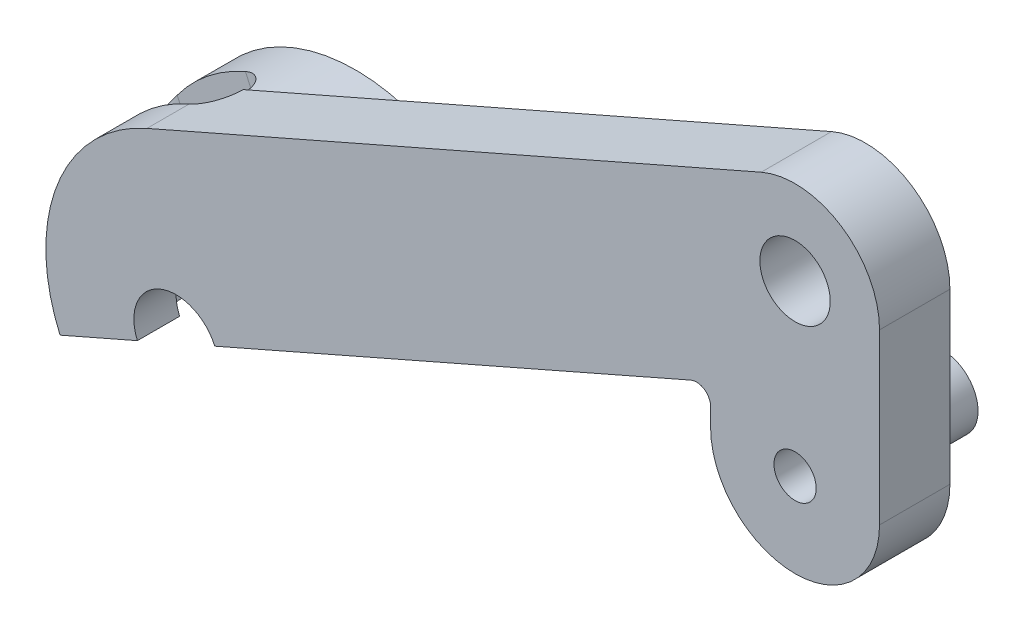
SolidWorks part; units mm, degrees
ref_plane "Plano frontal" through (0, 0, 0) normal (0, 0, 1) x (1, 0, 0)
ref_plane "Plano superior" through (0, 0, 0) normal (0, 1, 0) x (1, 0, 0)
ref_plane "Plano direito" through (0, 0, 0) normal (1, 0, 0) x (0, 0, -1)
sketch "Esboço7" plane through (0, 0, 0) normal (0, 0, 1) x (1, 0, 0)
  line L0 (0, 0) -> (0, -12) construction
  line L1 (6, 0) -> (6, -12)
  line L2 (-7.4014, -9.7942) -> (-41.2219, -24.6148)
  line L3 (0, 0) -> (-50.3755, -22.0751) construction
  line L4 (-46.1864, -20.7604) -> (-43.9697, -25.8189) construction
  line L5 (-2.4082, 5.4955) -> (-46.0383, -13.6238)
  line L6 (-6, -10.7101) -> (-6, -12)
  line L7 (-42.0163, -22.7728) -> (-47.4902, -25.2194) construction
  line L8 (-46.7174, -27.023) -> (-52.213, -29.4312)
  circle A0 centre (0, 0) radius 2.5
  arc A1 (-6, -12) -> (6, -12) centre (0, -12) ccw
  arc A2 (6, 0) -> (-2.4082, 5.4955) centre (0, 0) ccw
  arc A3 (-46.0383, -13.6238) -> (-52.213, -29.4312) centre (-41.2219, -24.6148) ccw
  arc A5 (-41.2219, -24.6148) -> (-46.7174, -27.023) centre (-43.9697, -25.8189) ccw
  arc A6 (-6, -10.7101) -> (-7.4014, -9.7942) centre (-7, -10.7101) ccw
  point P4 (0, -6)
  point P11 (-25.1877, -11.0376)
  dimension "D1" = 1
extrude "Ressalto-extrusão1" add sketch "Esboço7" along normal blind 5
sketch "Esboço8" plane through (0, 0, 0) normal (0, 0, -1) x (-1, 0, 0)
  circle A0 centre (0, -12) radius 2.5
extrude "Ressalto-extrusão2" add sketch "Esboço8" along normal blind 5.5
sketch "Esboço9" plane through (0, 0, -5.5) normal (0, 0, -1) x (-1, 0, 0)
  circle A0 centre (0, -12) radius 1.5
extrude "Corte-extrusão4" cut sketch "Esboço9" against normal blind 25
sketch "Esboço10" plane through (0, 0, 0) normal (0, 0, -1) x (-1, 0, 0)
  line L0 (46.7174, -27.023) -> (52.213, -29.4312)
  line L1 (41.2219, -24.6148) -> (30.2309, -19.7984)
  line L2 (41.2219, -24.6148) -> (7.4014, -9.7942) construction
  arc A0 (52.213, -29.4312) -> (30.2309, -19.7984) centre (41.2219, -24.6148) ccw
  arc A1 (46.7174, -27.023) -> (41.2219, -24.6148) centre (43.9697, -25.8189) ccw
extrude "Ressalto-extrusão3" add sketch "Esboço10" along normal blind 5
sketch "Esboço11" plane through (-2.4082, 5.4955, 0) normal (-0.4014, 0.9159, 0) x (-0.9159, -0.4014, 0)
  line L0 (47.6354, 0) -> (53.6354, 0) construction
  line L1 (47.6354, 5) -> (47.6354, -5) construction
  line L2 (53.6354, 5) -> (53.6354, -5) construction
  line L3 (47.6354, 2) -> (53.6354, 2)
  line L4 (47.6354, -2) -> (53.6354, -2)
  arc A0 (47.6354, 2) -> (47.6354, -2) centre (47.6354, 0) ccw
  arc A1 (53.6354, -2) -> (53.6354, 2) centre (53.6354, 0) ccw
  point P6 (50.6354, 0)
extrude "Corte-extrusão5" cut sketch "Esboço11" against normal blind 16
sketch "Sketch1" plane through (0, 0, 0) normal (0, 0, -1) x (-1, 0, 0)
  circle A0 centre (0, -12) radius 3.5
  circle A1 centre (0, -12) radius 2.5
extrude "Boss-Extrude1" add sketch "Sketch1" along normal blind 0.5
